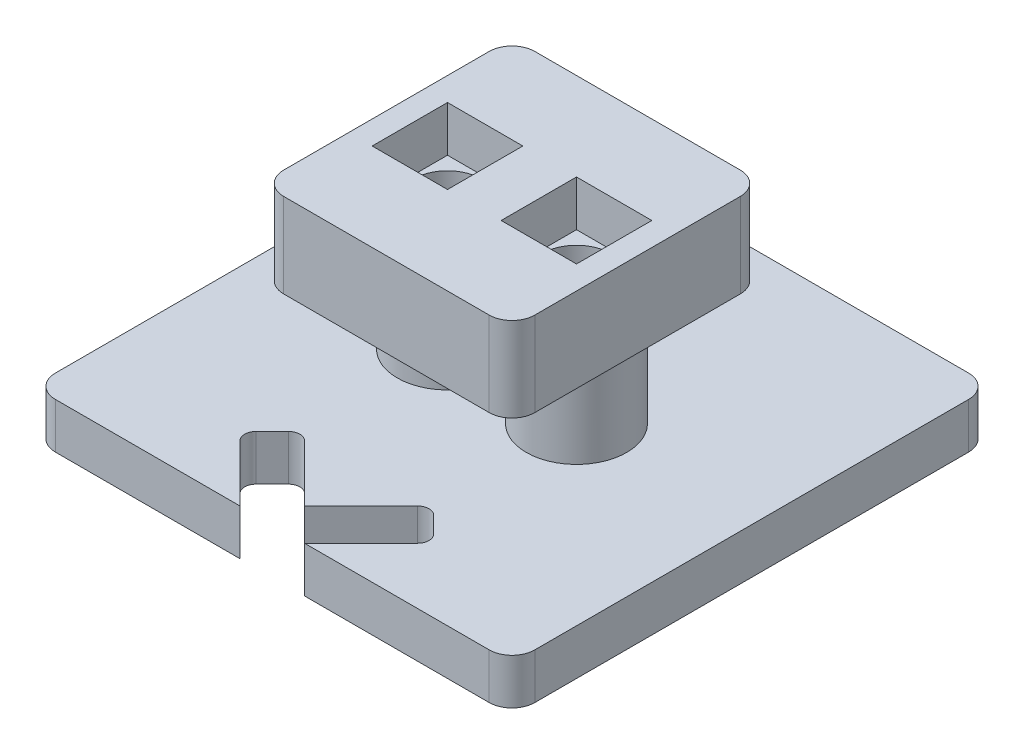
SolidWorks part; units mm, degrees
ref_plane "Front Plane" through (0, 0, 0) normal (0, 0, 1) x (1, 0, 0)
ref_plane "Top Plane" through (0, 0, 0) normal (0, 1, 0) x (1, 0, 0)
ref_plane "Right Plane" through (0, 0, 0) normal (1, 0, 0) x (0, 0, -1)
sketch "Sketch1" plane through (0, 0, 0) normal (0, 1, 0) x (1, 0, 0)
  line L1 (-5.5, -5.5) -> (5.5, -5.5)
  line L2 (-5.5, -5.5) -> (-5.5, 5.5)
  line L3 (-5.5, 5.5) -> (5.5, 5.5)
  line L4 (5.5, -5.5) -> (5.5, 5.5)
  line L5 (-5.5, -5.5) -> (5.5, 5.5) construction
  line L6 (-5.5, 5.5) -> (5.5, -5.5) construction
  point P0 (0, 0)
  dimension "D1" = 11
  dimension "D2" = 11
extrude "Boss-Extrude1" add sketch "Sketch1" along normal blind 3.7
fillet "Fillet1" radius 1 4 edges at (-5.5, 1.85, -5.5) (-5.5, 1.85, 5.5) (5.5, 1.85, -5.5) (5.5, 1.85, 5.5)
sketch "Sketch2" plane through (0, 3.7, 0) normal (0, 1, 0) x (1, 0, 0)
  line L0 (-2.825, 0) -> (2.825, 0) construction
  line L2 (-4.475, -1.65) -> (-1.175, -1.65)
  line L3 (-4.475, -1.65) -> (-4.475, 1.65)
  line L4 (-4.475, 1.65) -> (-1.175, 1.65)
  line L5 (-1.175, -1.65) -> (-1.175, 1.65)
  line L6 (-4.475, -1.65) -> (-1.175, 1.65) construction
  line L7 (-4.475, 1.65) -> (-1.175, -1.65) construction
  line L8 (1.175, -1.65) -> (4.475, -1.65)
  line L9 (1.175, -1.65) -> (1.175, 1.65)
  line L10 (1.175, 1.65) -> (4.475, 1.65)
  line L11 (4.475, -1.65) -> (4.475, 1.65)
  line L12 (1.175, -1.65) -> (4.475, 1.65) construction
  line L13 (1.175, 1.65) -> (4.475, -1.65) construction
  point P4 (0, 0)
  dimension "D1" = 3.3
  dimension "D2" = 3.3
  dimension "D3" = 3.3
  dimension "D4" = 3.3
  dimension "D5" = 5.65
extrude "Cut-Extrude1" cut sketch "Sketch2" against normal blind 2
sketch "Sketch4" plane through (0, 0, 0) normal (0, -1, 0) x (-1, 0, 0)
  line L0 (2.825, 0) -> (-2.825, 0) construction
  circle A0 centre (2.825, 0) radius 2.2
  circle A1 centre (-2.825, 0) radius 2.2
  point P4 (0, 0)
  point P8 (0, 0)
  dimension "D1" = 5.65
  dimension "D2" = 4.4
  dimension "D3" = 4.4
extrude "Boss-Extrude2" add sketch "Sketch4" along normal blind 6
sketch "Sketch5" plane through (0, -6, 0) normal (0, -1, 0) x (-1, 0, 0)
  line L1 (9.5, 10.5) -> (-9.5, 10.5)
  line L2 (10.5, 9.5) -> (10.5, -9.5)
  line L3 (9.5, -10.5) -> (-9.5, -10.5)
  line L4 (-10.5, 9.5) -> (-10.5, -9.5)
  line L5 (10.5, 10.5) -> (-10.5, -10.5) construction
  line L6 (10.5, -10.5) -> (-10.5, 10.5) construction
  arc A0 (10.5, -9.5) -> (9.5, -10.5) centre (9.5, -9.5) cw
  arc A1 (-10.5, -9.5) -> (-9.5, -10.5) centre (-9.5, -9.5) ccw
  arc A2 (-9.5, 10.5) -> (-10.5, 9.5) centre (-9.5, 9.5) ccw
  arc A3 (9.5, 10.5) -> (10.5, 9.5) centre (9.5, 9.5) cw
  point P0 (0, 0)
  dimension "D3" = 1
  dimension "D1" = 21
  dimension "D2" = 21
extrude "Boss-Extrude3" add sketch "Sketch5" against normal blind 2
sketch "Sketch3" plane through (0, 3.7, 0) normal (0, 1, 0) x (1, 0, 0)
  line L0 (-2.825, 0) -> (2.825, 0) construction
  circle A0 centre (-2.825, 0) radius 1.5
  circle A1 centre (2.825, 0) radius 1.5
  point P4 (0, 0)
  point P5 (0, 0)
  point P8 (0, 0)
  dimension "D2" = 3
  dimension "D3" = 3
  dimension "D1" = 5.65
extrude "Cut-Extrude2" cut sketch "Sketch3" against normal through all
sketch "Sketch7" plane through (0, -4, 0) normal (0, 1, 0) x (1, 0, 0)
  line L0 (9.5, -10.5) -> (-9.5, -10.5) construction
  line L1 (2.8284, -14.7426) -> (4.2426, -13.3284)
  line L2 (2.8284, -14.7426) -> (-3.8891, -8.0251)
  line L3 (-3.8891, -7.318) -> (-3.182, -6.6109)
  line L4 (4.2426, -13.3284) -> (-2.4749, -6.6109)
  line L5 (2.8284, -14.7426) -> (-2.8284, -6.2574) construction
  line L6 (-4.2426, -7.6716) -> (4.2426, -13.3284) construction
  line L8 (-4.2426, -13.3284) -> (-2.8284, -14.7426)
  line L9 (-4.2426, -13.3284) -> (2.4749, -6.6109)
  line L10 (3.182, -6.6109) -> (3.8891, -7.318)
  line L11 (-2.8284, -14.7426) -> (3.8891, -8.0251)
  line L12 (-4.2426, -13.3284) -> (4.2426, -7.6716) construction
  line L13 (2.8284, -6.2574) -> (-2.8284, -14.7426) construction
  arc A0 (-2.4749, -6.6109) -> (-3.182, -6.6109) centre (-2.8284, -6.9645) ccw
  arc A1 (3.8891, -7.318) -> (3.8891, -8.0251) centre (3.5355, -7.6716) cw
  arc A2 (3.182, -6.6109) -> (2.4749, -6.6109) centre (2.8284, -6.9645) ccw
  arc A3 (-3.8891, -7.318) -> (-3.8891, -8.0251) centre (-3.5355, -7.6716) ccw
  point P0 (0, -10.5)
  point P7 (0, -10.5)
  point P12 (-1.4142, -10.5)
  point P13 (1.4142, -10.5)
  line M12 (-9.5, -10.5) -> (9.5, -10.5)
  dimension "D7" = 0.5
  dimension "D8" = 0.5
  dimension "D1" = 2
  dimension "D2" = 45
  dimension "D3" = 2
  dimension "D4" = 45
  dimension "D5" = 4
  dimension "D6" = 4
extrude "Cut-Extrude3" cut sketch "Sketch7" against normal through all contours L10 A2 L9 L4 L11 A1 | L3 A3 L2 L9 L4 A0 | L9 L4 M12
equation "\"D2@Sketch2\"=\"D1@Sketch2\""
equation "\"D3@Sketch2\"=\"D1@Sketch2\""
equation "\"D4@Sketch2\"=\"D1@Sketch2\""
equation "\"D2@Sketch1\"=\"D1@Sketch1\""
equation "\"D3@Sketch3\"=\"D2@Sketch3\""
equation "\"D3@Sketch4\"=\"D2@Sketch4\""
equation "\"D2@Sketch5\"=\"D1@Sketch5\""
equation "\"D3@Sketch7\"=\"D1@Sketch7\""
equation "\"D6@Sketch7\"=\"D5@Sketch7\""
